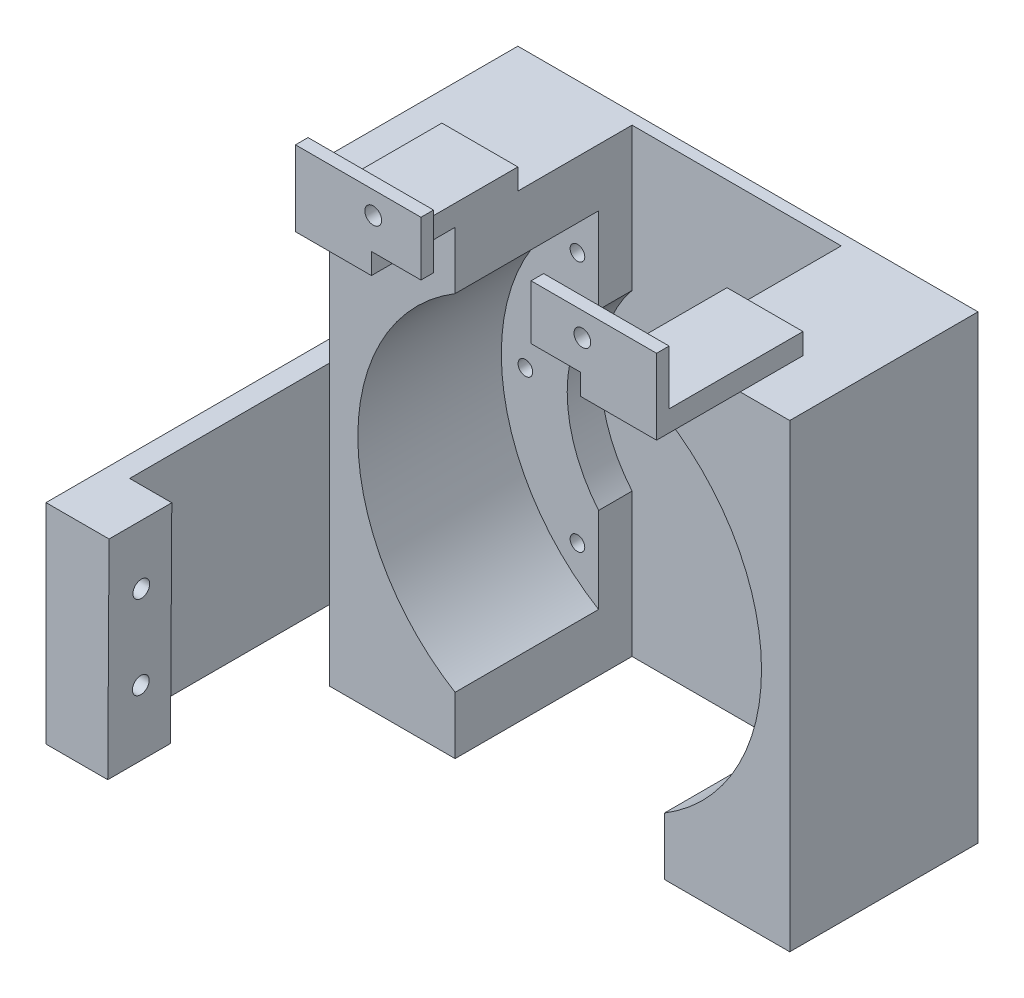
SolidWorks part; units mm, degrees
ref_plane "前视基准面" through (0, 0, 0) normal (0, 0, 1) x (1, 0, 0)
ref_plane "上视基准面" through (0, 0, 0) normal (0, 1, 0) x (1, 0, 0)
ref_plane "右视基准面" through (0, 0, 0) normal (1, 0, 0) x (0, 0, -1)
sketch "草图1" plane through (0, 0, 0) normal (0, 0, 1) x (1, 0, 0)
  line L1 (0, 0) -> (110, 0)
  line L2 (0, 0) -> (0, -110)
  line L3 (0, -110) -> (110, -110)
  line L4 (110, 0) -> (110, -110)
  dimension "D1" = 110
  dimension "D2" = 110
extrude "凸台-拉伸1" add sketch "草图1" along normal blind 45
sketch "草图3" plane through (0, 0, 45) normal (0, 0, 1) x (1, 0, 0)
  line L4 (0, 0) -> (0, -110)
  line L5 (0, -110) -> (110, -110)
  line L6 (110, -110) -> (110, 0)
  line L7 (110, 0) -> (0, 0)
  line L8 (0, 0) -> (0, -110)
  line L9 (0, -110) -> (110, -110)
  line L10 (110, -110) -> (110, 0)
  line L11 (110, 0) -> (0, 0)
  dimension "D1" = 0
sketch "草图4" plane through (0, 0, 45) normal (0, 0, 1) x (1, 0, 0)
  line L0 (0, -55) -> (110, -55) construction
  line L1 (0, 0) -> (0, -110) construction
  line L2 (110, -110) -> (110, 0) construction
  line L3 (55, -110) -> (55, -55) construction
  line L4 (0, -110) -> (110, -110) construction
  circle A0 centre (55, -55) radius 32.5
  dimension "D1" = 65
extrude "切除-拉伸1" cut sketch "草图4" against normal blind 42.3 contours A0
sketch "草图5" plane through (0, 0, 45) normal (0, 0, 1) x (1, 0, 0)
  line L4 (0, 0) -> (0, -110)
  line L5 (0, -110) -> (110, -110)
  line L6 (110, -110) -> (110, 0)
  line L7 (110, 0) -> (0, 0)
  line L8 (0, 0) -> (0, -110) construction
  line L9 (0, -110) -> (110, -110) construction
  line L10 (110, -110) -> (110, 0) construction
  line L11 (110, 0) -> (0, 0) construction
  circle A0 centre (55, -55) radius 48.25
  circle A1 centre (55, -55) radius 32.5
  circle A2 centre (55, -55) radius 32.5 construction
  dimension "D3" = 96.5
  dimension "D1" = 0
  dimension "D2" = 0
extrude "切除-拉伸2" cut sketch "草图5" against normal blind 34.3
sketch "草图6" plane through (0, 0, 10.7) normal (0, 0, 1) x (1, 0, 0)
  line L0 (30, -110) -> (30, 0)
  line L1 (30, -110) -> (80, -110)
  line L2 (30, 0) -> (80, 0)
  line L3 (80, -110) -> (80, 0)
  line L4 (30, -110) -> (80, 0) construction
  line L5 (30, 0) -> (80, -110) construction
  circle A1 centre (55, -55) radius 32.5
  circle A2 centre (55, -55) radius 32.5 construction
  dimension "D2" = 50
  dimension "D3" = 110
  dimension "D1" = 0
extrude "切除-拉伸3" cut sketch "草图6" against normal up to surface (8 mm away) up to face at (87.5, -55, 2.7)
sketch "草图7" plane through (0, 0, 45) normal (0, 0, 1) x (1, 0, 0)
  line L6 (80, -34.2334) -> (80, 0)
  line L7 (80, 0) -> (30, 0)
  line L8 (30, 0) -> (30, -34.2334)
  line L9 (30, -75.7666) -> (30, -110)
  line L10 (30, -110) -> (80, -110)
  line L11 (80, -110) -> (80, -75.7666)
  line L12 (80, -34.2334) -> (80, 0)
  line L13 (80, 0) -> (30, 0)
  line L14 (30, 0) -> (30, -34.2334)
  line L15 (30, -75.7666) -> (30, -110)
  line L16 (30, -110) -> (80, -110)
  line L17 (80, -110) -> (80, -75.7666)
  arc A2 (80, -75.7666) -> (80, -34.2334) centre (55, -55) ccw
  arc A3 (30, -34.2334) -> (30, -75.7666) centre (55, -55) ccw
  arc A4 (80, -75.7666) -> (80, -34.2334) centre (55, -55) ccw
  arc A5 (30, -34.2334) -> (30, -75.7666) centre (55, -55) ccw
  dimension "D1" = 0
extrude "切除-拉伸4" cut sketch "草图7" against normal up to surface (42.3 mm away) up to face at (55, -55, 2.7)
sketch "草图8" plane through (0, 0, 10.7) normal (0, 0, 1) x (1, 0, 0)
  line L2 (30, -34.2334) -> (30, -13.7318)
  line L3 (30, -96.2682) -> (30, -75.7666)
  line L4 (30, -34.2334) -> (30, -13.7318) construction
  line L5 (30, -96.2682) -> (30, -75.7666) construction
  circle A0 centre (55, -55) radius 42.5 construction
  circle A1 centre (12.5, -55) radius 1.75
  arc A2 (30, -13.7318) -> (30, -96.2682) centre (55, -55) ccw
  arc A3 (30, -34.2334) -> (30, -75.7666) centre (55, -55) ccw
  arc A4 (30, -13.7318) -> (30, -96.2682) centre (55, -55) ccw construction
  arc A5 (30, -34.2334) -> (30, -75.7666) centre (55, -55) ccw construction
  circle A6 centre (24.948, -24.948) radius 1.75
  circle A8 centre (85.052, -24.948) radius 1.75
  circle A9 centre (97.5, -55) radius 1.75
  circle A10 centre (85.052, -85.052) radius 1.75
  circle A12 centre (24.948, -85.052) radius 1.75
  circle A13 centre (55, -12.5) radius 1.75 [skipped]
  circle A14 centre (55, -97.5) radius 1.75 [skipped]
  point P26 (55, -55)
  dimension "D2" = 85
  dimension "D3" = 3.5
  dimension "D1" = 0
  dimension "D4" = 8
extrude "切除-拉伸5" cut sketch "草图8" against normal through all
sketch "草图9" plane through (0, 0, 0) normal (0, 1, 0) x (1, 0, 0)
  line L0 (30, -45) -> (0, -45) construction
  line L1 (11.8414, -45) -> (30, -45)
  line L2 (11.8414, -45) -> (11.8414, -30)
  line L3 (11.8414, -30) -> (30, -30)
  line L4 (30, -45) -> (30, -30)
  line L5 (30, -2.7) -> (30, -45) construction
  line L6 (55, 0) -> (55, -58.6504) construction
  line L7 (11.8414, -45) -> (30, -45)
  line L8 (11.8414, -45) -> (11.8414, -65)
  line L9 (11.8414, -65) -> (30, -65)
  line L10 (30, -45) -> (30, -65)
  line L11 (110, 0) -> (0, 0) construction
  line L12 (98.1586, -65) -> (80, -65)
  line L13 (80, -45) -> (80, -65)
  line L14 (98.1586, -45) -> (80, -45)
  line L15 (98.1586, -45) -> (98.1586, -65)
  line L16 (98.1586, -30) -> (80, -30)
  line L17 (80, -45) -> (80, -30)
  line L18 (98.1586, -45) -> (80, -45)
  line L19 (98.1586, -45) -> (98.1586, -30)
  line M6 (0, -45) -> (30, -45)
  line M7 (30, -45) -> (30, -2.7)
  line M9 (80, -2.7) -> (80, -45)
  line M10 (80, -45) -> (110, -45)
  dimension "D1" = 15
  dimension "D2" = 20
extrude "凸台-拉伸2" add sketch "草图9" along normal blind 5 contours L3 L2 M6 M7 | L10 L8 L9 M6 | L19 L16 M10 M9 | L15 L13 L12 M10
sketch "草图10" plane through (0, 5, 0) normal (0, 1, 0) x (1, 0, 0)
  line L0 (98.1586, -65) -> (98.1586, -30) construction
  line L1 (98.1586, -62) -> (68.1586, -62)
  line L2 (98.1586, -62) -> (98.1586, -65)
  line L3 (98.1586, -65) -> (68.1586, -65)
  line L4 (68.1586, -62) -> (68.1586, -65)
  line L7 (11.8414, -65) -> (11.8414, -30) construction
  line L8 (11.8414, -62) -> (41.8414, -62)
  line L9 (11.8414, -62) -> (11.8414, -65)
  line L10 (11.8414, -65) -> (41.8414, -65)
  line L11 (41.8414, -62) -> (41.8414, -65)
  line L13 (11.8414, -65) -> (30, -65) construction
  dimension "D1" = 3
  dimension "D2" = 30
  dimension "D3" = 30
  dimension "D4" = 3
  dimension "D5" = 0
extrude "凸台-拉伸3" add sketch "草图10" along normal blind 13
sketch "草图11" plane through (0, 0, 62) normal (0, 0, -1) x (-1, 0, 0)
  circle A1 centre (-30.4257, 12.6561) radius 2
  circle A3 centre (-80.4247, 12.3412) radius 2
extrude "切除-拉伸6" cut sketch "草图11" against normal through all
sketch "草图12" plane through (0, 0, 0) normal (-1, 0, 0) x (0, 0, 1)
  line L1 (22.7964, -93.093) -> (107.7964, -93.093)
  line L2 (22.7964, -93.093) -> (22.7964, -43.093)
  line L3 (22.7964, -43.093) -> (107.7964, -43.093)
  line L4 (107.7964, -93.093) -> (107.7964, -43.093)
  dimension "D1" = 50
  dimension "D2" = 85
extrude "凸台-拉伸4" add sketch "草图12" along normal blind 5
sketch "草图13" plane through (0, 0, 0) normal (1, 0, 0) x (0, 0, -1)
  line L0 (-107.7964, -43.093) -> (-45, -43.093) construction
  line L1 (-92.7964, -43.093) -> (-107.7964, -43.093)
  line L2 (-92.7964, -43.093) -> (-92.7964, -93.093)
  line L3 (-92.7964, -93.093) -> (-107.7964, -93.093)
  line L4 (-107.7964, -43.093) -> (-107.7964, -93.093)
  line L5 (-45, -93.093) -> (-107.7964, -93.093) construction
  dimension "D1" = 15
extrude "凸台-拉伸5" add sketch "草图13" along normal up to surface (10.0741 mm away)
sketch "草图15" plane through (-5, 0, 0) normal (-1, 0, 0) x (0, 0, 1)
  ellipse E3 centre (100, -57.3479) end of major axis (98, -57.3479) minor radius 2
  ellipse E4 centre (100, -77.3479) end of major axis (98, -77.3479) minor radius 2 (102, -77.3479) -> (98, -77.3479) ccw
  ellipse E5 centre (100, -77.3479) end of major axis (98, -77.3479) minor radius 2 (98, -77.3479) -> (102, -77.3479) ccw
extrude "切除-拉伸8" cut sketch "草图15" against normal up to surface (14.8583 mm away)
